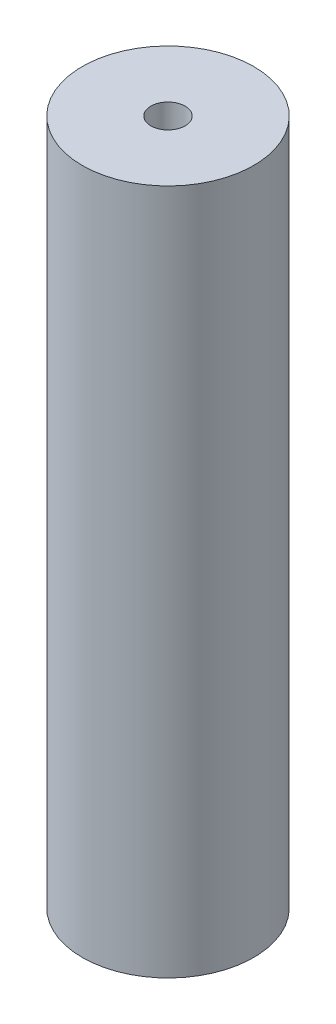
SolidWorks part; units mm, degrees
ref_plane "Plan de face" through (0, 0, 0) normal (0, 0, 1) x (1, 0, 0)
ref_plane "Plan de dessus" through (0, 0, 0) normal (0, 1, 0) x (1, 0, 0)
ref_plane "Plan de droite" through (0, 0, 0) normal (1, 0, 0) x (0, 0, -1)
sketch "Esquisse1" plane through (0, 0, 0) normal (0, 1, 0) x (1, 0, 0)
  circle A0 centre (0, 0) radius 10
extrude "Boss.-Extru.1" add sketch "Esquisse1" along normal blind 80
sketch "Esquisse9" plane through (0, 80, 0) normal (0, 1, 0) x (1, 0, 0)
  circle A0 centre (0, 0) radius 2
extrude "Enlèv. mat.-Extru.1" cut sketch "Esquisse9" against normal blind 20
sketch "Esquisse10" plane through (0, 0, 0) normal (0, -1, 0) x (-1, 0, 0)
  circle A0 centre (0, 0) radius 1.505
extrude "Enlèv. mat.-Extru.2" cut sketch "Esquisse10" against normal blind 15
